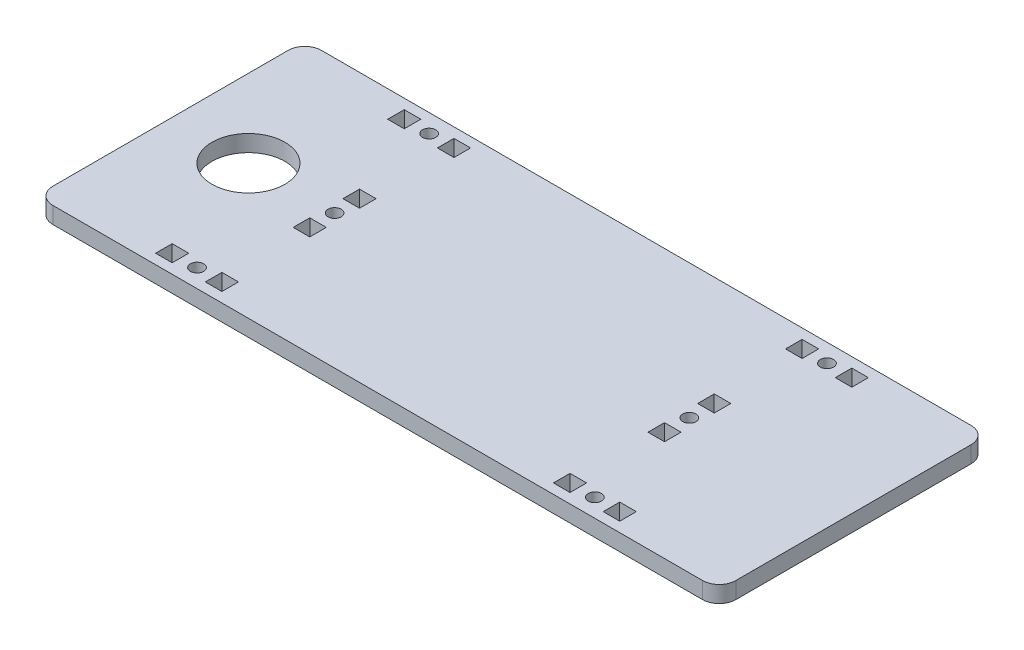
SolidWorks part; units mm, degrees
ref_plane "Front Plane" through (0, 0, 0) normal (0, 0, 1) x (1, 0, 0)
ref_plane "Top Plane" through (0, 0, 0) normal (0, 1, 0) x (1, 0, 0)
ref_plane "Right Plane" through (0, 0, 0) normal (1, 0, 0) x (0, 0, -1)
sketch "Sketch1" plane through (0, 0, 0) normal (0, 1, 0) x (1, 0, 0)
  line L0 (5.1027, 53.6563) -> (5.1027, -27.3437) construction
  line L1 (-97.8973, 53.6563) -> (108.1027, 53.6563)
  line L2 (-97.8973, 53.6563) -> (-97.8973, -27.3437)
  line L3 (-97.8973, -27.3437) -> (108.1027, -27.3437)
  line L4 (108.1027, 53.6563) -> (108.1027, -27.3437)
  line L5 (-97.8973, 13.1563) -> (108.1027, 13.1563) construction
  line L6 (60.1027, 45.6563) -> (55.1027, 45.6563)
  line L7 (-64.8973, 50.6563) -> (-59.8973, 50.6563)
  line L8 (-64.8973, 50.6563) -> (-64.8973, 45.6563)
  line L9 (-64.8973, 45.6563) -> (-59.8973, 45.6563)
  line L10 (-59.8973, 50.6563) -> (-59.8973, 45.6563)
  line L11 (-49.8973, 50.6563) -> (-44.8973, 50.6563)
  line L12 (-49.8973, 50.6563) -> (-49.8973, 45.6563)
  line L13 (-49.8973, 45.6563) -> (-44.8973, 45.6563)
  line L14 (-44.8973, 50.6563) -> (-44.8973, 45.6563)
  line L15 (55.1027, 50.6563) -> (55.1027, 45.6563)
  line L16 (60.1027, 50.6563) -> (55.1027, 50.6563)
  line L17 (60.1027, 50.6563) -> (60.1027, 45.6563)
  line L18 (70.1027, 50.6563) -> (70.1027, 45.6563)
  line L19 (75.1027, 50.6563) -> (70.1027, 50.6563)
  line L20 (75.1027, 50.6563) -> (75.1027, 45.6563)
  line L21 (75.1027, 45.6563) -> (70.1027, 45.6563)
  line L22 (75.1027, -24.3437) -> (75.1027, -19.3437)
  line L23 (75.1027, -19.3437) -> (70.1027, -19.3437)
  line L24 (75.1027, -24.3437) -> (70.1027, -24.3437)
  line L25 (70.1027, -24.3437) -> (70.1027, -19.3437)
  line L26 (60.1027, -24.3437) -> (60.1027, -19.3437)
  line L27 (60.1027, -19.3437) -> (55.1027, -19.3437)
  line L28 (55.1027, -24.3437) -> (55.1027, -19.3437)
  line L29 (60.1027, -24.3437) -> (55.1027, -24.3437)
  line L30 (-49.8973, -24.3437) -> (-44.8973, -24.3437)
  line L31 (-44.8973, -24.3437) -> (-44.8973, -19.3437)
  line L32 (-49.8973, -19.3437) -> (-44.8973, -19.3437)
  line L33 (-49.8973, -24.3437) -> (-49.8973, -19.3437)
  line L34 (-64.8973, -24.3437) -> (-59.8973, -24.3437)
  line L35 (-64.8973, -24.3437) -> (-64.8973, -19.3437)
  line L36 (-64.8973, -19.3437) -> (-59.8973, -19.3437)
  line L37 (-59.8973, -24.3437) -> (-59.8973, -19.3437)
  line L42 (-45.8973, 18.1563) -> (-45.8973, 23.1563)
  line L43 (-50.8973, 8.1563) -> (-45.8973, 8.1563)
  line L44 (-50.8973, 8.1563) -> (-50.8973, 3.1563)
  line L45 (-50.8973, 3.1563) -> (-45.8973, 3.1563)
  line L46 (-45.8973, 8.1563) -> (-45.8973, 3.1563)
  line L47 (-50.8973, 23.1563) -> (-45.8973, 23.1563)
  line L48 (-50.8973, 18.1563) -> (-50.8973, 23.1563)
  line L49 (-50.8973, 18.1563) -> (-45.8973, 18.1563)
  line L50 (56.1027, 8.1563) -> (56.1027, 3.1563)
  line L51 (61.1027, 3.1563) -> (56.1027, 3.1563)
  line L52 (61.1027, 8.1563) -> (61.1027, 3.1563)
  line L53 (61.1027, 8.1563) -> (56.1027, 8.1563)
  line L54 (56.1027, 18.1563) -> (56.1027, 23.1563)
  line L55 (61.1027, 18.1563) -> (56.1027, 18.1563)
  line L56 (61.1027, 18.1563) -> (61.1027, 23.1563)
  line L57 (61.1027, 23.1563) -> (56.1027, 23.1563)
  circle A0 centre (-54.8973, 48.1563) radius 2
  circle A1 centre (-54.8973, -21.8437) radius 2
  circle A2 centre (65.1027, -21.8437) radius 2
  circle A3 centre (65.1027, 48.1563) radius 2
  circle A5 centre (-48.3973, 13.1563) radius 2
  circle A6 centre (58.6027, 13.1563) radius 2
  circle A7 centre (-74.3973, 13.1563) radius 11
  point P36 (-59.8973, -19.3437)
  point P55 (-45.8973, 5.6563)
  dimension "D7" = 4
  dimension "D8" = 4
  dimension "D12" = 22
  dimension "D1" = 206
  dimension "D2" = 81
  dimension "D3" = 5
  dimension "D4" = 10
  dimension "D5" = 3
  dimension "D6" = 50
  dimension "D9" = 51
  dimension "D10" = 5
  dimension "D11" = 5.5
extrude "Boss-Extrude4" add sketch "Sketch1" along normal blind 5
fillet "Fillet9" radius 5 4 edges at (108.1027, 2.5, -53.6563) (108.1027, 2.5, 27.3437) (-97.8973, 2.5, -53.6563) (-97.8973, 2.5, 27.3437)
sketch "Sketch2" plane through (0, 5, 0) normal (0, 1, 0) x (1, 0, 0)
  line L0 (-40.5649, -10.5366) -> (49.4351, -10.5366)
  line L1 (49.4351, -10.5366) -> (49.4351, 21.8634)
  line L2 (49.4351, 21.8634) -> (27.5201, 43.7784)
  line L3 (4.4351, -10.5366) -> (4.4351, 0.2738) construction
  line L4 (-40.5649, -10.5366) -> (-40.5649, 21.8634)
  line L5 (-40.5649, 21.8634) -> (-18.6499, 43.7784)
  line L6 (-18.6499, 43.7784) -> (27.5201, 43.7784)
  line L7 (46.3751, 20.5959) -> (46.3751, -7.4766)
  line L8 (46.3751, -7.4766) -> (-37.5049, -7.4766)
  line L9 (46.3751, 20.5959) -> (26.2526, 40.7184)
  line L10 (26.2526, 40.7184) -> (-17.3824, 40.7184)
  line L11 (43.3151, 19.3284) -> (43.3151, -4.4166)
  line L12 (43.3151, -4.4166) -> (-34.4449, -4.4166)
  line L13 (43.3151, 19.3284) -> (24.9851, 37.6584)
  line L14 (24.9851, 37.6584) -> (-16.1149, 37.6584)
  line L15 (-8.7049, 29.1984) -> (17.5751, 29.1984)
  line L16 (-11.7649, 32.2584) -> (20.6351, 32.2584)
  line L17 (20.6351, 32.2584) -> (20.6351, 19.2084)
  line L18 (20.6351, 19.2084) -> (12.1751, 19.2084)
  line L19 (12.1751, 19.2084) -> (12.1751, -0.5466)
  line L20 (12.1751, -0.5466) -> (-3.3049, -0.5466)
  line L21 (17.5751, 29.1984) -> (17.5751, 22.2684)
  line L22 (17.5751, 22.2684) -> (9.1151, 22.2684)
  line L23 (9.1151, 22.2684) -> (9.1151, 2.5134)
  line L24 (9.1151, 2.5134) -> (-0.2449, 2.5134)
  line L25 (-34.4449, 19.3284) -> (-34.4449, -4.4166)
  line L26 (-37.5049, 20.5959) -> (-37.5049, -7.4766)
  line L27 (-34.4449, 19.3284) -> (-16.1149, 37.6584)
  line L28 (-37.5049, 20.5959) -> (-17.3824, 40.7184)
  line L29 (-11.7649, 32.2584) -> (-11.7649, 19.2084)
  line L30 (-11.7649, 19.2084) -> (-3.3049, 19.2084)
  line L31 (-3.3049, 19.2084) -> (-3.3049, -0.5466)
  line L32 (-0.2449, 22.2684) -> (-0.2449, 2.5134)
  line L33 (-8.7049, 22.2684) -> (-0.2449, 22.2684)
  line L34 (-8.7049, 29.1984) -> (-8.7049, 22.2684)
  line L35 (4.4351, 98.0934) -> (4.4351, -10.5366)
  line L36 (-59.6981, 16.6234) -> (95.9131, 16.6234) construction
  line L41 (108.1027, -22.3437) -> (108.1027, 48.6563)
  line L42 (103.1027, 53.6563) -> (-92.8973, 53.6563)
  line L43 (-97.8973, 48.6563) -> (-97.8973, -22.3437)
  line L44 (-92.8973, -27.3437) -> (103.1027, -27.3437)
  line L45 (108.1027, -22.3437) -> (108.1027, 48.6563)
  line L46 (103.1027, 53.6563) -> (-92.8973, 53.6563)
  line L47 (-97.8973, 48.6563) -> (-97.8973, -22.3437)
  line L48 (-92.8973, -27.3437) -> (103.1027, -27.3437)
  arc A4 (108.1027, 48.6563) -> (103.1027, 53.6563) centre (103.1027, 48.6563) ccw
  arc A5 (-92.8973, 53.6563) -> (-97.8973, 48.6563) centre (-92.8973, 48.6563) ccw
  arc A6 (-97.8973, -22.3437) -> (-92.8973, -27.3437) centre (-92.8973, -22.3437) ccw
  arc A7 (103.1027, -27.3437) -> (108.1027, -22.3437) centre (103.1027, -22.3437) ccw
  arc A8 (108.1027, 48.6563) -> (103.1027, 53.6563) centre (103.1027, 48.6563) ccw
  arc A9 (-92.8973, 53.6563) -> (-97.8973, 48.6563) centre (-92.8973, 48.6563) ccw
  arc A10 (-97.8973, -22.3437) -> (-92.8973, -27.3437) centre (-92.8973, -22.3437) ccw
  arc A11 (103.1027, -27.3437) -> (108.1027, -22.3437) centre (103.1027, -22.3437) ccw
  point P13 (4.4351, 37.6584)
  point P31 (4.4351, -7.4766)
  point P32 (4.4351, -4.4166)
  point P36 (4.4351, 40.7184)
  point P37 (4.4351, 32.2584)
  point P40 (4.4351, -0.5466)
  point P41 (4.4351, 2.5134)
  point P44 (4.4351, 29.1984)
  point P47 (4.4351, 43.7784)
  dimension "D1" = 90
  dimension "D2" = 32.4
  dimension "D3" = 46.17
  dimension "D4" = 45
  dimension "D5" = 3.06
  dimension "D6" = 3.06
  dimension "D7" = 3.06
  dimension "D8" = 3.06
  dimension "D9" = 3.06
  dimension "D10" = 3.06
  dimension "D11" = 3.06
  dimension "D12" = 3.06
  dimension "D13" = 5.4
  dimension "D14" = 16.2
  dimension "D15" = 13.05
  dimension "D16" = 8.46
  dimension "D17" = 3.87
  dimension "D18" = 3.06
  dimension "D19" = 3.06
  dimension "D20" = 3.06
  dimension "D21" = 3.06
  dimension "D22" = 3.06
  dimension "D23" = 27.16
  dimension "D24" = 0
